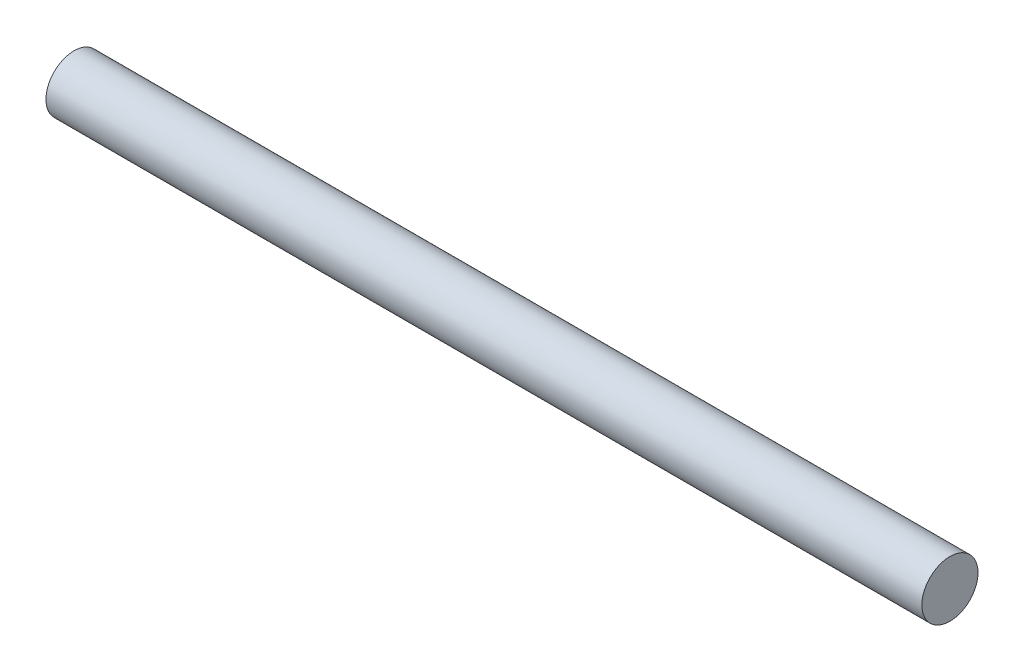
SolidWorks part; units mm, degrees
ref_plane "Front Plane" through (0, 0, 0) normal (0, 0, 1) x (1, 0, 0)
ref_plane "Top Plane" through (0, 0, 0) normal (0, 1, 0) x (1, 0, 0)
ref_plane "Right Plane" through (0, 0, 0) normal (1, 0, 0) x (0, 0, -1)
sketch "Sketch1" plane through (0, 0, 0) normal (1, 0, 0) x (0, 0, -1)
  circle A0 centre (0, 0) radius 6.35
extrude "Boss-Extrude1" add sketch "Sketch1" along normal blind 198.12
